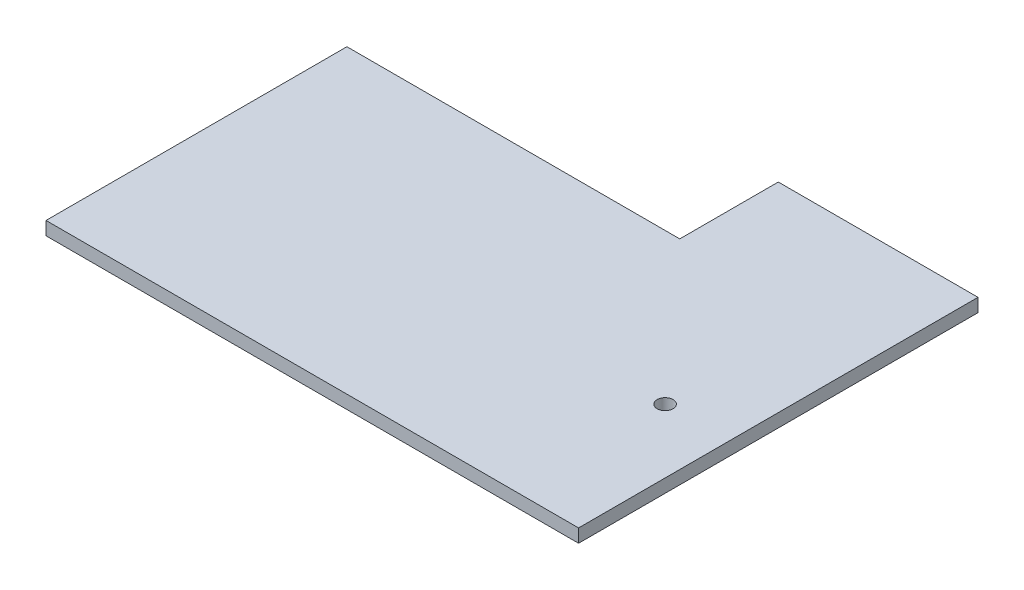
SolidWorks part; units mm, degrees
ref_plane "Front Plane" through (0, 0, 0) normal (0, 0, 1) x (1, 0, 0)
ref_plane "Top Plane" through (0, 0, 0) normal (0, 1, 0) x (1, 0, 0)
ref_plane "Right Plane" through (0, 0, 0) normal (1, 0, 0) x (0, 0, -1)
sketch "Szkic1" plane through (0, 0, 0) normal (0, 1, 0) x (1, 0, 0)
  line L0 (91.2344, 21.5) -> (70.2344, 21.5)
  line L1 (91.2344, -30) -> (-108.7656, -30)
  line L2 (91.2344, -30) -> (91.2344, 73)
  line L3 (91.2344, 73) -> (-108.7656, 73)
  line L4 (-108.7656, -30) -> (-108.7656, 73)
  line L5 (91.2344, -30) -> (-108.7656, 73) construction
  line L6 (91.2344, 73) -> (-108.7656, -30) construction
  line L7 (67.2344, 21.5) -> (67.2344, 110)
  line L8 (67.2344, 110) -> (91.2344, 110)
  line L9 (91.2344, 110) -> (91.2344, 73)
  line L10 (91.2344, 110) -> (21.2344, 110)
  line L11 (21.2344, 110) -> (21.2344, 73)
  line L12 (21.2344, 110) -> (21.2344, 115)
  line L13 (21.2344, 115) -> (91.2344, 115)
  line L14 (91.2344, 115) -> (91.2344, 110)
  line L15 (21.2344, 115) -> (16.2344, 115)
  line L16 (16.2344, 115) -> (16.2344, 73)
  line L17 (16.2344, 73) -> (16.2344, 78)
  line L18 (91.2344, -30) -> (91.2344, -35)
  line L19 (91.2344, -35) -> (-108.7656, -35)
  line L20 (16.2344, 78) -> (-108.7656, 78)
  line L21 (-108.7656, 78) -> (-108.7656, 73)
  line L22 (-108.7656, -35) -> (-108.7656, -30)
  line L23 (91.2344, -35) -> (91.2344, -30)
  circle A0 centre (67.2344, 21.5) radius 3
  point P0 (-8.7656, 21.5)
  dimension "D4" = 6
  dimension "D7" = 5
  dimension "D1" = 103
  dimension "D2" = 200
  dimension "D3" = 21
  dimension "D5" = 5
  dimension "D6" = 70
extrude "Dodanie-wyciągnięcie1" add sketch "Szkic1" against normal blind 5 contours L22 L19 L18 L1 | L10 L11 L3 L7 | L9 L8 L7 L3 | L20 L21 L3 L16 | L15 L16 L3 L11 L12 | L14 L13 L12 L10 L8 | A0 L7 L3 L4 L1 L2 L0 | A0 L0 L2 L3 L7
